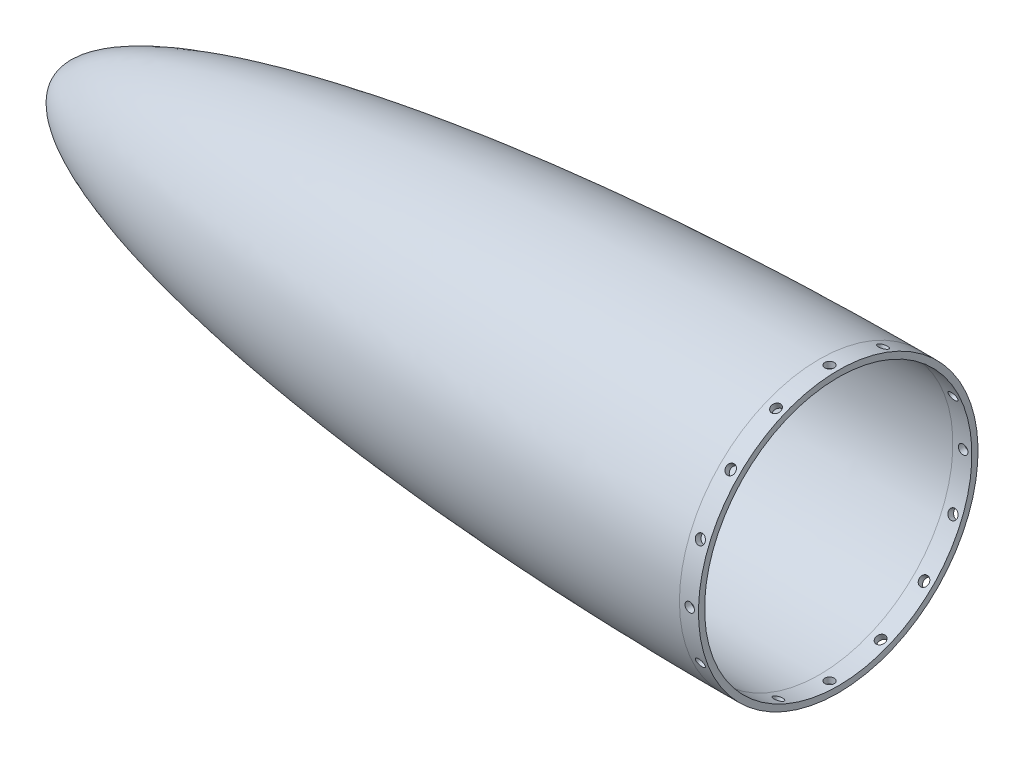
SolidWorks part; units mm, degrees
material "VeroWhite Plus"
ref_plane "Front Plane" through (0, 0, 0) normal (0, 0, 1) x (1, 0, 0)
ref_plane "Top Plane" through (0, 0, 0) normal (0, 1, 0) x (1, 0, 0)
ref_plane "Right Plane" through (0, 0, 0) normal (1, 0, 0) x (0, 0, -1)
sketch "Sketch1" plane through (0, 0, 0) normal (0, 0, 1) x (1, 0, 0)
  line L1 (-92, 0) -> (0, 0) construction
  line L5 (-92, 0) -> (-345.44, 0) construction
  line L14 (-345.44, 0) -> (-342.646, 0)
  line L16 (0, 63.5) -> (8.636, 63.5)
  line L18 (8.636, 63.5) -> (8.636, 60.706)
  line L19 (8.636, 60.706) -> (0, 60.706)
  ellipse E1 centre (0, 0) end of major axis (-345.44, 0) minor radius 63.5 (0, 63.5) -> (-345.44, 0) ccw
  spline S0 degree 1 poles (0, 60.706) (-342.646, 0) knots 0 0 1 1 construction
  spline S1 degree 3 poles (0, 60.706) (-11.2699, 60.706) (-33.8713, 60.5021) (-67.3964, 59.5877) (-100.2826, 58.0735) (-142.8332, 55.275) (-192.8184, 50.3637) (-245.3434, 42.4389) (-281.1864, 34.407) (-304.2411, 27.3341) (-318.5391, 21.7743) (-329.6722, 16.0481) (-336.1763, 11.2536) (-339.6668, 7.5428) (-341.4445, 4.8798) (-342.4384, 2.3654) (-342.646, 0.8053) (-342.646, 0) knots -1.570796 -1.570796 -1.570796 -1.570796 -1.472622 -1.374447 -1.276272 -1.178097 -0.981748 -0.785398 -0.589049 -0.490874 -0.392699 -0.294524 -0.19635 -0.147262 -0.098175 -0.049087 0 0 0 0
  dimension "D1" = 2.794
  dimension "D2" = 8.636
  dimension "D4" = 345.44
  dimension "D3" = 63.5
revolve "Revolve1" add sketch "Sketch1" angle 360 about L1
ref_plane "Plane1" through (8.636, 0, 0) normal (1, 0, 0) x (0, 0, -1)
hole_wizard "#6 Clearance Hole1" positions "3DSketch3" profile "Sketch4" hole size "#6" standard "ANSI Inch" end condition through all
sketch3d "3DSketch3"
  point P0 (4.6736, 63.5, 0)
  dimension "D1" = 3.9624
sketch "Sketch4" plane through (4.6736, 63.5, 0) normal (1, 0, 0) x (0, 0, 1)
  line L0 (0, 0) -> (0, 127)
  line L1 (0, 127) -> (2.1526, 127)
  line L2 (2.1526, 127) -> (2.1526, 0)
  line L5 (2.1526, 0) -> (0, 0)
  line L11 (0, -6.35) -> (0, 107.95) construction
  dimension "Thru Hole Dia." = 4.3053
  dimension "Thru Hole Depth" = 127
pattern_circular "CirPattern1" count 16 over 360 about axis through (8.636, 0, 0) along (-1, 0, 0) of "#6 Clearance Hole1"
